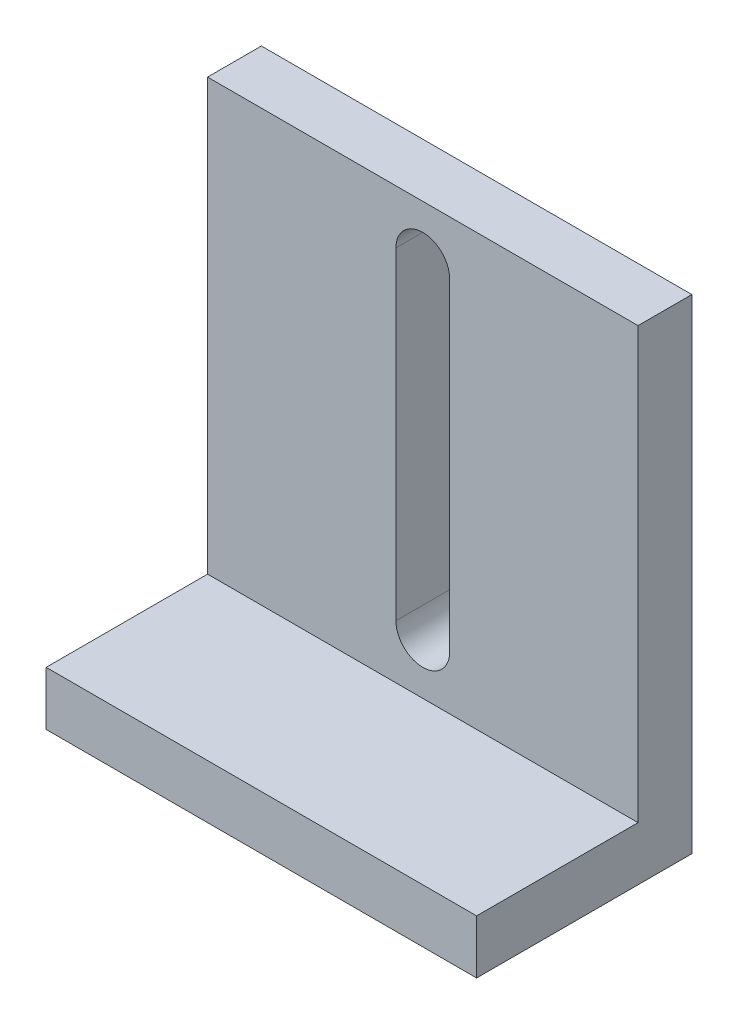
SolidWorks part; units mm, degrees
material "6061 Alloy"
ref_plane "Front Plane" through (0, 0, 0) normal (0, 0, 1) x (1, 0, 0)
ref_plane "Top Plane" through (0, 0, 0) normal (0, 1, 0) x (1, 0, 0)
ref_plane "Right Plane" through (0, 0, 0) normal (1, 0, 0) x (0, 0, -1)
sketch "Sketch1" plane through (0, 0, 0) normal (0, 1, 0) x (1, 0, 0)
  line L1 (12.7, -6.35) -> (-12.7, -6.35)
  line L2 (12.7, -6.35) -> (12.7, 6.35)
  line L3 (12.7, 6.35) -> (-12.7, 6.35)
  line L4 (-12.7, -6.35) -> (-12.7, 6.35)
  line L5 (12.7, -6.35) -> (-12.7, 6.35) construction
  line L6 (12.7, 6.35) -> (-12.7, -6.35) construction
  point P0 (0, 0)
  dimension "D1" = 25.4
  dimension "D2" = 12.7
extrude "Boss-Extrude1" add sketch "Sketch1" along normal blind 3.175
sketch "Sketch2" plane through (0, 3.175, 0) normal (0, 1, 0) x (1, 0, 0)
  line L0 (12.7, -6.35) -> (12.7, 6.35) construction
  line L1 (-12.7, 6.35) -> (12.7, 6.35)
  line L2 (-12.7, 6.35) -> (-12.7, 3.175)
  line L3 (-12.7, 3.175) -> (12.7, 3.175)
  line L4 (12.7, 6.35) -> (12.7, 3.175)
  dimension "D1" = 3.175
extrude "Boss-Extrude2" add sketch "Sketch2" along normal blind 25.4
sketch "Sketch3" plane through (0, 0, -3.175) normal (0, 0, 1) x (1, 0, 0)
  line L0 (0, 25.4) -> (0, 6.35) construction
  line L1 (1.5875, 25.4) -> (1.5875, 6.35)
  line L2 (-1.5875, 25.4) -> (-1.5875, 6.35)
  line L3 (-12.7, 28.575) -> (12.7, 28.575) construction
  arc A0 (1.5875, 25.4) -> (-1.5875, 25.4) centre (0, 25.4) ccw
  arc A1 (-1.5875, 6.35) -> (1.5875, 6.35) centre (0, 6.35) ccw
  point P3 (0, 15.875)
  dimension "D1" = 3.175
  dimension "D2" = 19.05
  dimension "D3" = 3.175
extrude "Cut-Extrude1" cut sketch "Sketch3" against normal through all
